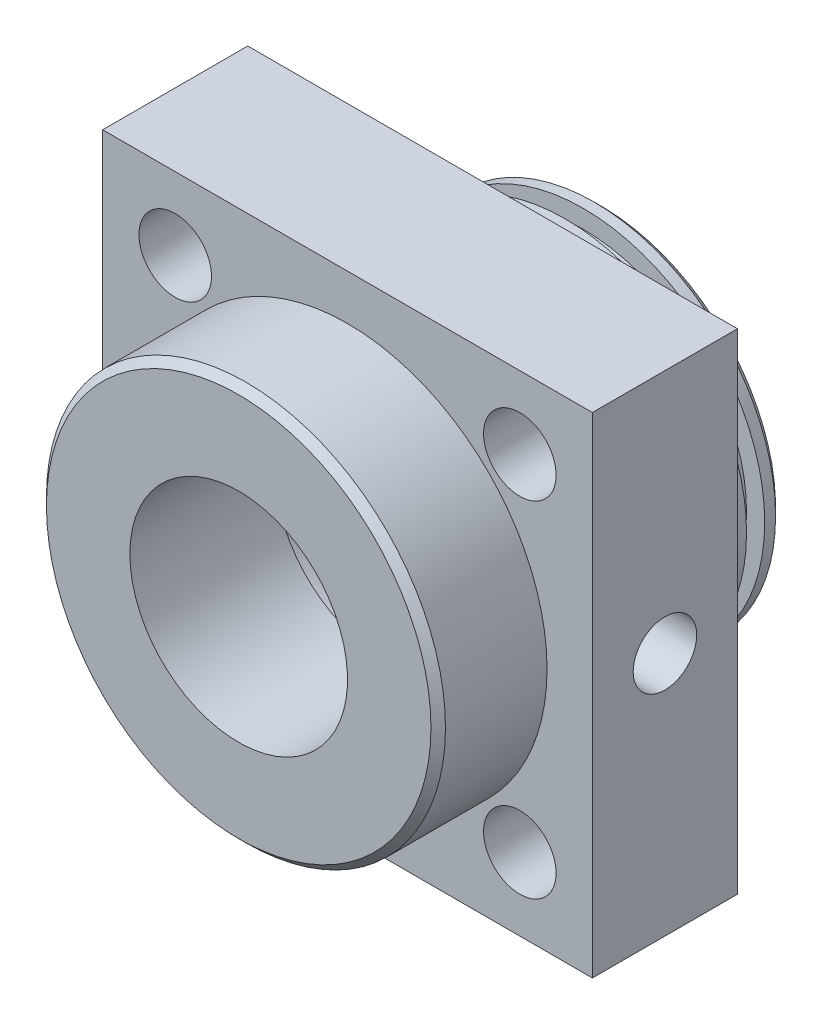
SolidWorks part; units mm, degrees
ref_plane "Front Plane" through (0, 0, 0) normal (0, 0, 1) x (1, 0, 0)
ref_plane "Top Plane" through (0, 0, 0) normal (0, 1, 0) x (1, 0, 0)
ref_plane "Right Plane" through (0, 0, 0) normal (1, 0, 0) x (0, 0, -1)
sketch "Sketch1" plane through (0, 0, 0) normal (0, 0, 1) x (1, 0, 0)
  circle A0 centre (0, 0) radius 55
  dimension "D1" = 110
extrude "Boss-Extrude1" add sketch "Sketch1" along normal blind 30
sketch "Sketch2" plane through (0, 0, 0) normal (0, 0, -1) x (-1, 0, 0)
  line L1 (-67.5, -67.5) -> (67.5, -67.5)
  line L2 (-67.5, -67.5) -> (-67.5, 67.5)
  line L3 (-67.5, 67.5) -> (67.5, 67.5)
  line L4 (67.5, -67.5) -> (67.5, 67.5)
  line L5 (-67.5, -67.5) -> (67.5, 67.5) construction
  line L6 (-67.5, 67.5) -> (67.5, -67.5) construction
  point P0 (0, 0)
  dimension "D1" = 135
extrude "Boss-Extrude2" add sketch "Sketch2" along normal blind 40
sketch "Sketch3" plane through (0, 0, -40) normal (0, 0, -1) x (-1, 0, 0)
  line L0 (67.5, 67.5) -> (-67.5, 67.5) construction
  line L1 (-67.5, 67.5) -> (-67.5, -67.5) construction
  line L2 (0, 70.1055) -> (0, -72.0282) construction
  line L3 (-88.1085, 0) -> (74.0504, 0) construction
  circle A0 centre (-47.5, 47.5) radius 10
  circle A1 centre (47.5, 47.5) radius 10
  circle A2 centre (47.5, -47.5) radius 10
  circle A3 centre (-47.5, -47.5) radius 10
  dimension "D1" = 20
  dimension "D2" = 20
  dimension "D3" = 20
extrude "Cut-Extrude1" cut sketch "Sketch3" against normal blind 40
sketch "Sketch4" plane through (0, 0, -40) normal (0, 0, -1) x (-1, 0, 0)
  circle A0 centre (0, 0) radius 50
  dimension "D1" = 100
extrude "Boss-Extrude3" add sketch "Sketch4" along normal blind 20
sketch "Sketch5" plane through (0, 0, -60) normal (0, 0, -1) x (-1, 0, 0)
  circle A0 centre (0, 0) radius 45
  dimension "D1" = 90
extrude "Boss-Extrude4" add sketch "Sketch5" along normal blind 5
sketch "Sketch6" plane through (0, 0, -65) normal (0, 0, -1) x (-1, 0, 0)
  circle A0 centre (0, 0) radius 50
  dimension "D1" = 100
extrude "Boss-Extrude5" add sketch "Sketch6" along normal blind 5
chamfer "Chamfer1" distance 2 angle 45 1 edges at (55, 0, 30)
chamfer "Chamfer2" distance 2 angle 45 1 edges at (-50, 0, -70)
sketch "Sketch7" plane through (-67.5, 0, 0) normal (-1, 0, 0) x (0, 0, 1)
  line L1 (-40, 67.5) -> (0, 67.5) construction
  line L2 (-40, 67.5) -> (-40, -67.5) construction
  line L3 (-40, -67.5) -> (0, -67.5) construction
  line L4 (0, 67.5) -> (0, -67.5) construction
  line L5 (-40, 67.5) -> (0, -67.5) construction
  line L6 (-40, -67.5) -> (0, 67.5) construction
  circle A0 centre (-20, 0) radius 10
  point P4 (-20, 0)
  dimension "D1" = 20
hole_wizard "M20x2.5 Tapped Hole1" positions "Sketch7" profile "Sketch8" tap size "M20x2.5" standard "ANSI Metric" end condition through all
sketch "Sketch8" plane through (-67.5, 0, -20) normal (0, 1, 0) x (0, 0, 1)
  line L0 (0, 0) -> (0, 135)
  line L1 (0, 135) -> (8.75, 135)
  line L2 (8.75, 135) -> (8.75, 0)
  line L5 (8.75, 0) -> (0, 0)
  line L11 (0, -6.35) -> (0, 107.95) construction
  dimension "Thru Tap Drill Dia." = 17.5
  dimension "Thru Tap Drill Depth" = 135
cosmetic thread "Hole Thread1" parameters "D2"=20
sketch "Sketch9" plane through (0, 0, -70) normal (0, 0, -1) x (-1, 0, 0)
  circle A0 centre (0, 0) radius 35
  dimension "D1" = 70
extrude "Cut-Extrude2" cut sketch "Sketch9" against normal blind 60
sketch "Sketch10" plane through (0, 0, -10) normal (0, 0, -1) x (-1, 0, 0)
  circle A0 centre (0, 0) radius 30
  dimension "D1" = 60
extrude "Cut-Extrude3" cut sketch "Sketch10" against normal through all
